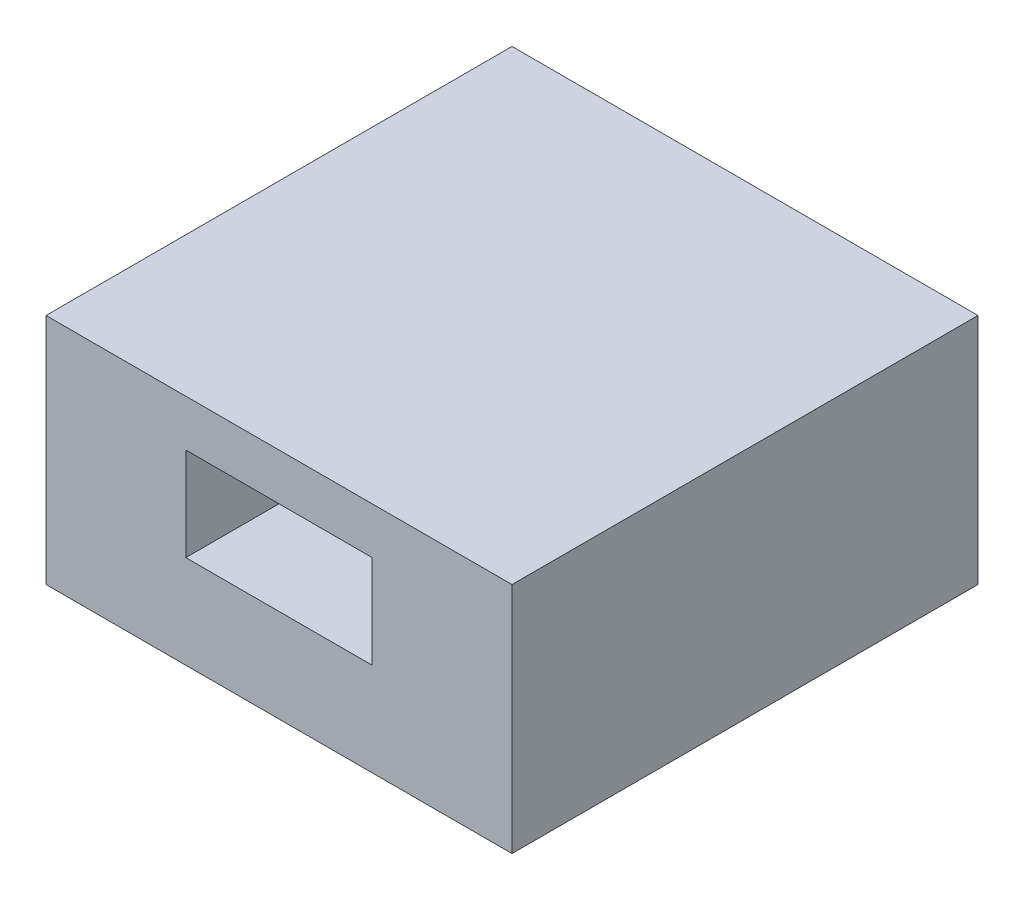
SolidWorks part; units mm, degrees
ref_plane "Front Plane" through (0, 0, 0) normal (0, 0, 1) x (1, 0, 0)
ref_plane "Top Plane" through (0, 0, 0) normal (0, 1, 0) x (1, 0, 0)
ref_plane "Right Plane" through (0, 0, 0) normal (1, 0, 0) x (0, 0, -1)
sketch "Sketch1" plane through (0, 0, 0) normal (0, 1, 0) x (1, 0, 0)
  line L0 (0, 107.7699) -> (0, -96.6326) construction
  line L1 (-113.3386, 0) -> (134.9581, 0) construction
  line L2 (25, 0) -> (-25, 0)
  line L3 (-25, 0) -> (-25, -50)
  line L4 (-25, -50) -> (25, -50)
  line L5 (25, 0) -> (25, -50)
  point P10 (0, -50)
  point P11 (0, 0)
  dimension "D1" = 25
  dimension "D2" = 50
extrude "Boss-Extrude1" add sketch "Sketch1" along normal blind 25
sketch "Sketch2" plane through (0, 0, 50) normal (0, 0, 1) x (1, 0, 0)
  line L0 (0, 39.6581) -> (0, -31.0186) construction
  line L1 (10, 20) -> (-10, 20)
  line L2 (-10, 20) -> (-10, 10)
  line L3 (-10, 10) -> (10, 10)
  line L4 (-42.4927, 0) -> (44.337, 0) construction
  line L5 (10, 20) -> (10, 10)
  point P10 (0, 10)
  point P11 (0, 20)
  dimension "D1" = 10
  dimension "D2" = 10
  dimension "D3" = 10
extrude "Cut-Extrude1" cut sketch "Sketch2" against normal blind 50
sketch "Sketch3" plane through (0, 10, 0) normal (0, 1, 0) x (1, 0, 0)
  line L0 (0, 22.4233) -> (0, -27.4848) construction
  line L1 (-32.7734, 0) -> (40.4092, 0) construction
  circle A0 centre (0, -8) radius 3
  dimension "D1" = 6
  dimension "D2" = 8
extrude "Cut-Extrude2" cut sketch "Sketch3" against normal blind 10
sketch "Sketch4" plane through (0, 10, 0) normal (0, 1, 0) x (1, 0, 0)
  line L0 (0, 26.1646) -> (0, -31.6694) construction
  line L1 (-38.1566, 0) -> (36.8842, 0) construction
  line L3 (2.8868, -3) -> (-2.8868, -3)
  line L4 (-2.8868, -3) -> (-5.7735, -8)
  line L5 (-5.7735, -8) -> (-2.8868, -13)
  line L6 (-2.8868, -13) -> (2.8868, -13)
  line L7 (2.8868, -13) -> (5.7735, -8)
  line L8 (5.7735, -8) -> (2.8868, -3)
  circle A0 centre (0, -8) radius 5 construction
  dimension "D2" = 10
  dimension "D1" = 8
extrude "Cut-Extrude3" cut sketch "Sketch4" against normal blind 5
